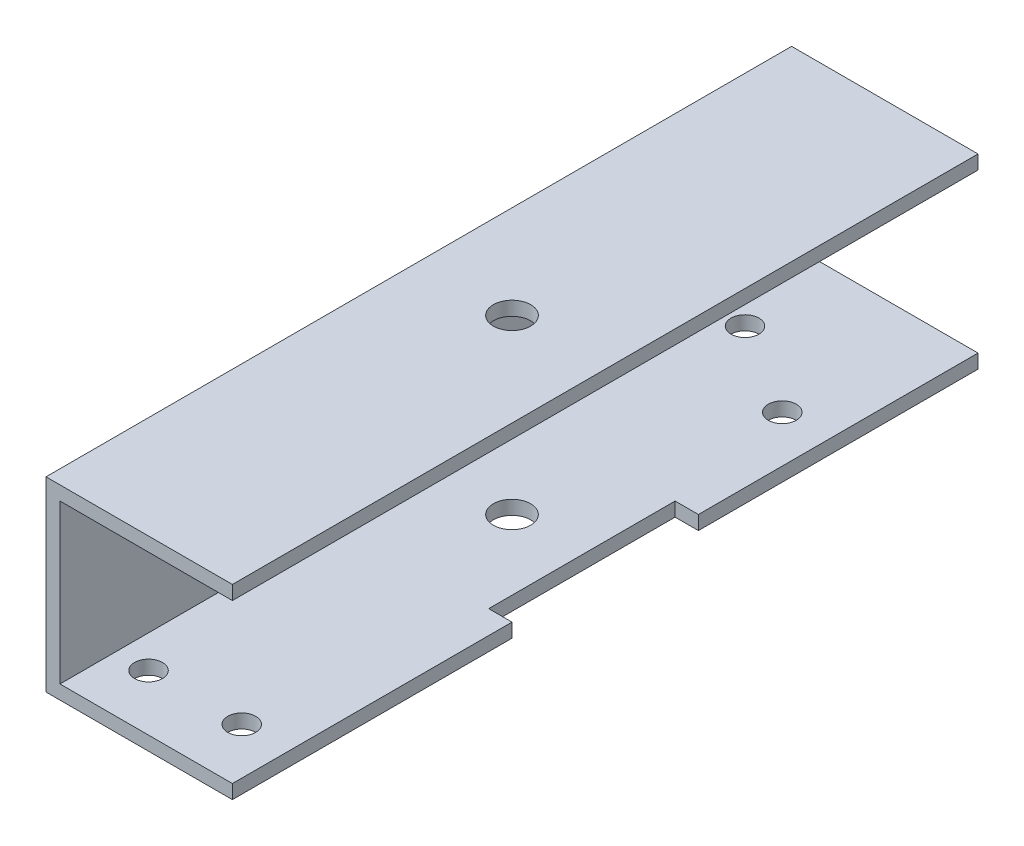
SolidWorks part; units mm, degrees
ref_plane "Plan de face" through (0, 0, 0) normal (0, 0, 1) x (1, 0, 0)
ref_plane "Plan de dessus" through (0, 0, 0) normal (0, 1, 0) x (1, 0, 0)
ref_plane "Plan de droite" through (0, 0, 0) normal (1, 0, 0) x (0, 0, -1)
sketch "Esquisse1" plane through (0, 0, 0) normal (0, 0, 1) x (1, 0, 0)
  line L0 (-29.2868, 30.6298) -> (-29.2868, 10.6298)
  line L1 (-29.2868, 10.6298) -> (-9.2868, 10.6298)
  line L2 (-9.2868, 12.1298) -> (-9.2868, 10.6298)
  line L4 (-27.7868, 29.1298) -> (-9.2868, 29.1298)
  line L5 (-9.2868, 12.1298) -> (-27.7868, 12.1298)
  line L6 (-27.7868, 12.1298) -> (-27.7868, 29.1298)
  line L7 (-9.2868, 29.1298) -> (-9.2868, 30.6298)
  line L8 (-9.2868, 30.6298) -> (-29.2868, 30.6298)
  dimension "D1" = 20
  dimension "D2" = 1.5
  dimension "D3" = 1.5
  dimension "D4" = 20
  dimension "D6" = 20
extrude "Extrusion1" add sketch "Esquisse1" along normal blind 80
sketch "Esquisse2" plane through (0, 10.6298, 0) normal (0, -1, 0) x (1, 0, 0)
  line L0 (-9.2868, 80) -> (-9.2868, 0) construction
  line L1 (-14.2868, 74) -> (-24.2868, 74) construction
  line L2 (-29.2868, 80) -> (-9.2868, 80) construction
  line L3 (-29.2868, 0) -> (-9.2868, 0) construction
  line L4 (-29.2868, 80) -> (-29.2868, 0) construction
  line L5 (-9.2868, 50) -> (-11.7868, 50)
  line L6 (-9.2868, 50) -> (-9.2868, 30)
  line L7 (-9.2868, 30) -> (-11.7868, 30)
  line L8 (-11.7868, 50) -> (-11.7868, 30)
  line L9 (-29.2868, 80) -> (-9.2868, 80) construction
  circle A0 centre (-14.2868, 74) radius 1.5
  circle A1 centre (-24.2868, 74) radius 1.5
  circle A2 centre (-14.2868, 16) radius 1.5
  circle A3 centre (-24.2868, 10) radius 1.5
  dimension "D1" = 10
  dimension "D4" = 6
  dimension "D6" = 2.5
  dimension "D2" = 5
  dimension "D3" = 6
  dimension "D5" = 10
  dimension "D7" = 20
  dimension "D8" = 30
extrude "Extrusion2" cut sketch "Esquisse2" against normal blind 10
sketch "Esquisse3" plane through (0, 10.6298, 0) normal (0, -1, 0) x (1, 0, 0)
  line L0 (-29.2868, 80) -> (-29.2868, 0) construction
  line L1 (-29.2868, 80) -> (-9.2868, 80) construction
  circle A0 centre (-19.2868, 40) radius 2
  dimension "D1" = 10
  dimension "D2" = 40
extrude "Extrusion3" cut sketch "Esquisse3" against normal through all
